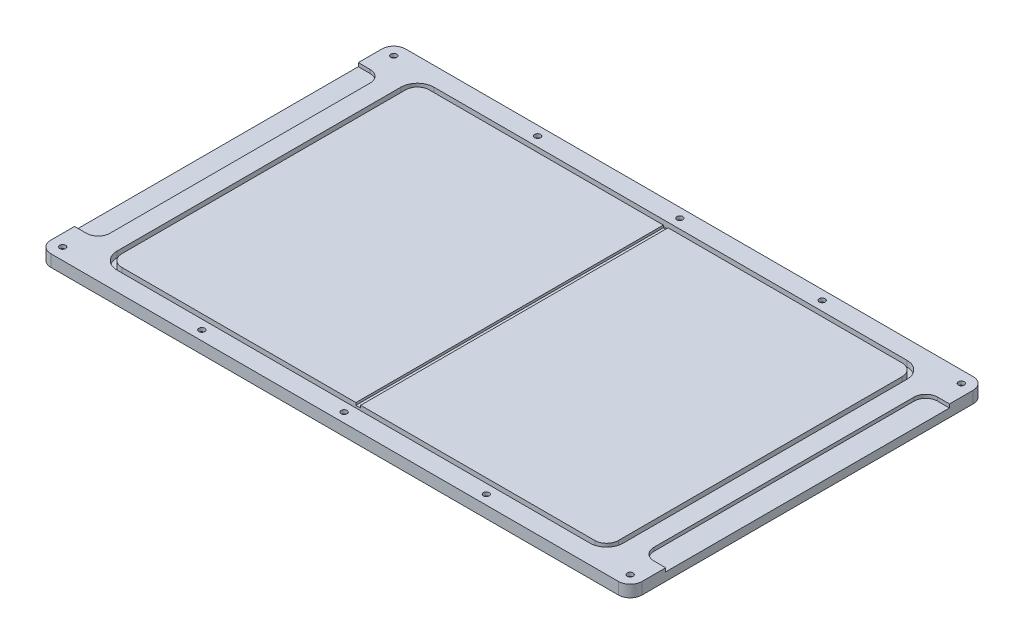
SolidWorks part; units mm, degrees
ref_plane "前视基准面" through (0, 0, 0) normal (0, 0, 1) x (1, 0, 0)
ref_plane "上视基准面" through (0, 0, 0) normal (0, 1, 0) x (1, 0, 0)
ref_plane "右视基准面" through (0, 0, 0) normal (1, 0, 0) x (0, 0, -1)
sketch "草图1" plane through (0, 0, 0) normal (0, 1, 0) x (1, 0, 0)
  line L1 (-120, 75) -> (120, 75)
  line L2 (-125, 70) -> (-125, -70)
  line L3 (-120, -75) -> (120, -75)
  line L4 (125, 70) -> (125, -70)
  line L5 (-125, 75) -> (125, -75) construction
  line L6 (-125, -75) -> (125, 75) construction
  arc A0 (125, 70) -> (120, 75) centre (120, 70) ccw
  arc A1 (125, -70) -> (120, -75) centre (120, -70) cw
  arc A2 (-125, -70) -> (-120, -75) centre (-120, -70) ccw
  arc A3 (-125, 70) -> (-120, 75) centre (-120, 70) cw
  point P0 (0, 0)
  dimension "D3" = 5
  dimension "D1" = 250
  dimension "D2" = 150
extrude "凸台-拉伸1" add sketch "草图1" along normal blind 5
sketch "草图2" plane through (0, 5, 0) normal (0, 1, 0) x (1, 0, 0)
  line L0 (-125, 70) -> (-125, -70) construction
  line L1 (-125, 60) -> (-120, 60)
  line L2 (-125, 60) -> (-125, -60)
  line L3 (-125, -60) -> (-120, -60)
  line L4 (-115, 55) -> (-115, -55)
  line L5 (0, 0) -> (0, 22.4955) construction
  line L6 (120, 75) -> (-120, 75) construction
  line L7 (-120, -75) -> (120, -75) construction
  line L8 (115, 55) -> (115, -55)
  line L9 (125, -60) -> (120, -60)
  line L10 (125, 60) -> (125, -60)
  line L11 (125, 60) -> (120, 60)
  arc A0 (-115, -55) -> (-120, -60) centre (-120, -55) cw
  arc A1 (-120, 60) -> (-115, 55) centre (-120, 55) cw
  arc A2 (120, 60) -> (115, 55) centre (120, 55) ccw
  arc A3 (115, -55) -> (120, -60) centre (120, -55) ccw
  point P11 (-122.5, -60)
  point P18 (-115, 60)
  point P27 (115, 60)
  dimension "D4" = 5
  dimension "D1" = 10
  dimension "D2" = 15
  dimension "D3" = 15
extrude "切除-拉伸1" cut sketch "草图2" against normal blind 1.5
sketch "草图3" plane through (0, 5, 0) normal (0, 1, 0) x (1, 0, 0)
  line L0 (120, 75) -> (-120, 75) construction
  line L1 (-100, 65) -> (100, 65)
  line L2 (-105, 60) -> (-105, -60)
  line L3 (-100, -65) -> (100, -65)
  line L4 (105, 60) -> (105, -60)
  line L5 (-105, 65) -> (105, -65) construction
  line L6 (-105, -65) -> (105, 65) construction
  line L7 (-115, -55) -> (-115, 55) construction
  line L8 (-100, 67) -> (100, 67)
  line L9 (107, 60) -> (107, -60)
  line L10 (-100, -67) -> (100, -67)
  line L11 (-107, 60) -> (-107, -60)
  arc A0 (105, -60) -> (100, -65) centre (100, -60) cw
  arc A1 (105, 60) -> (100, 65) centre (100, 60) ccw
  arc A2 (-105, -60) -> (-100, -65) centre (-100, -60) ccw
  arc A3 (-105, 60) -> (-100, 65) centre (-100, 60) cw
  arc A4 (107, 60) -> (100, 67) centre (100, 60) ccw
  arc A5 (107, -60) -> (100, -67) centre (100, -60) cw
  arc A6 (-107, -60) -> (-100, -67) centre (-100, -60) ccw
  arc A7 (-107, 60) -> (-100, 67) centre (-100, 60) cw
  point P1 (0, 0)
  dimension "D3" = 5
  dimension "D1" = 10
  dimension "D2" = 10
  dimension "D4" = 2
extrude "切除-拉伸2" cut sketch "草图3" against normal blind 2.5
sketch "草图4" plane through (0, 0, 0) normal (0, -1, 0) x (1, 0, 0)
  circle A0 centre (-120, 70) radius 1.25
  circle A1 centre (-120, -70) radius 1.25
  circle A2 centre (120, -70) radius 1.25
  circle A3 centre (120, 70) radius 1.25
  dimension "D1" = 2.5
  dimension "D2" = 2.5
  dimension "D3" = 2.5
  dimension "D4" = 2.5
extrude "切除-拉伸3" cut sketch "草图4" against normal blind 5
sketch "草图5" plane through (0, 0, 0) normal (0, -1, 0) x (1, 0, 0)
  circle A0 centre (-120, 70) radius 2.85
  circle A1 centre (-120, -70) radius 2.85
  circle A2 centre (120, -70) radius 2.85
  circle A3 centre (120, 70) radius 2.85
  dimension "D1" = 5.7
  dimension "D2" = 5.7
  dimension "D3" = 5.7
  dimension "D4" = 5.7
extrude "切除-拉伸4" cut sketch "草图5" against normal blind 3.5
sketch "草图6" plane through (0, 5, 0) normal (0, 1, 0) x (1, 0, 0)
  line L0 (0, 0) -> (0, 41.3894) construction
  line L1 (120, 75) -> (-120, 75) construction
  line L2 (120, 75) -> (-120, 75) construction
  line L3 (0, 0) -> (-38.2176, 0) construction
  circle A0 centre (0, 71) radius 1.25
  circle A1 centre (-60.1647, 71) radius 1.25
  circle A2 centre (60.1647, 71) radius 1.25
  circle A3 centre (60.1647, -71) radius 1.25
  circle A4 centre (-60.1647, -71) radius 1.25
  circle A5 centre (0, -71) radius 1.25
  dimension "D1" = 2.5
  dimension "D3" = 2.5
  dimension "D2" = 4
  dimension "D4" = 4
extrude "切除-拉伸5" cut sketch "草图6" against normal blind 5
sketch "草图7" plane through (0, 0, 0) normal (0, -1, 0) x (1, 0, 0)
  line L0 (0, 0) -> (9.1868, 0) construction
  circle A0 centre (-60.1647, 71) radius 2.85
  circle A1 centre (0, 71) radius 2.85
  circle A2 centre (60.1647, 71) radius 2.85
  circle A3 centre (60.1647, -71) radius 2.85
  circle A4 centre (0, -71) radius 2.85
  circle A5 centre (-60.1647, -71) radius 2.85
  dimension "D1" = 5.7
  dimension "D2" = 5.7
  dimension "D3" = 5.7
extrude "切除-拉伸6" cut sketch "草图7" against normal blind 3.5
sketch "草图8" plane through (0, 5, 0) normal (0, 1, 0) x (1, 0, 0)
  line L0 (0, 0) -> (0, 24.9282) construction
  line L1 (100, 65) -> (-100, 65) construction
  line L2 (-1, 65) -> (1, 65)
  line L3 (-1, 65) -> (-1, -65)
  line L4 (-1, -65) -> (1, -65)
  line L5 (1, 65) -> (1, -65)
  line L6 (-100, -65) -> (100, -65) construction
  dimension "D1" = 2
  dimension "D2" = 1
extrude "切除-拉伸8" cut sketch "草图8" against normal blind 1 contours L3 L4 L5 L2
